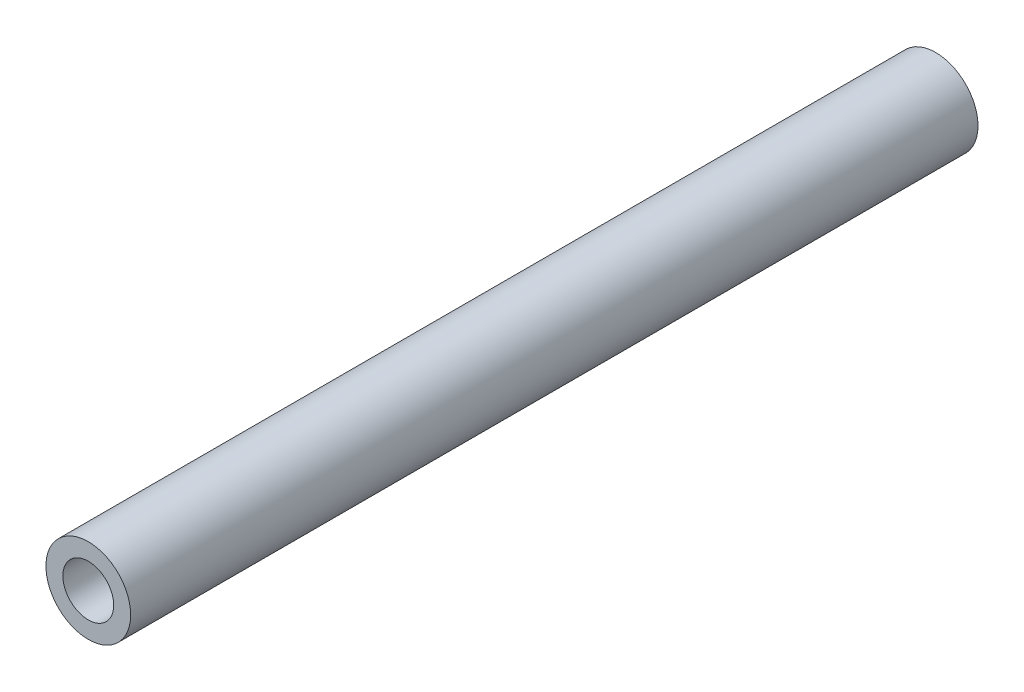
SolidWorks part; units mm, degrees
material "1060 Alloy"
ref_plane "Front Plane" through (0, 0, 0) normal (0, 0, 1) x (1, 0, 0)
ref_plane "Top Plane" through (0, 0, 0) normal (0, 1, 0) x (1, 0, 0)
ref_plane "Right Plane" through (0, 0, 0) normal (1, 0, 0) x (0, 0, -1)
sketch "Sketch1" plane through (0, 0, 0) normal (0, 0, 1) x (1, 0, 0)
  circle A0 centre (0, 0) radius 2.5
  dimension "D1" = 5
extrude "Boss-Extrude2" add sketch "Sketch1" along normal blind 50 contours A0
sketch "Sketch2" plane through (0, 0, 50) normal (0, 0, 1) x (1, 0, 0)
  circle A0 centre (0, 0) radius 1.5
  dimension "D1" = 3
extrude "Cut-Extrude1" cut sketch "Sketch2" against normal blind 6 contours A0
sketch "Sketch3" plane through (0, 0, 0) normal (0, 0, -1) x (-1, 0, 0)
  circle A0 centre (0, 0) radius 1.5
extrude "Cut-Extrude2" cut sketch "Sketch3" against normal blind 6 contours A0
